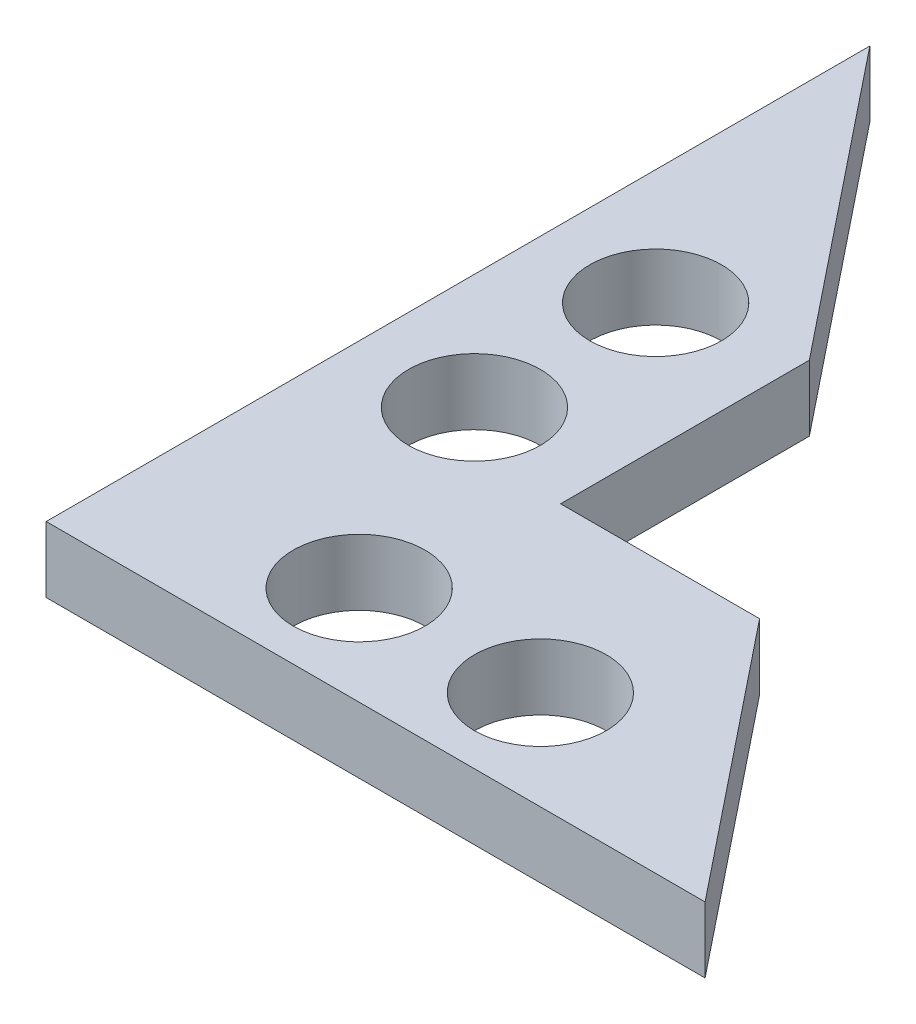
SolidWorks part; units mm, degrees
ref_plane "Front Plane" through (0, 0, 0) normal (0, 0, 1) x (1, 0, 0)
ref_plane "Top Plane" through (0, 0, 0) normal (0, 1, 0) x (1, 0, 0)
ref_plane "Right Plane" through (0, 0, 0) normal (1, 0, 0) x (0, 0, -1)
sketch "Sketch1" plane through (0, 0, 0) normal (0, 1, 0) x (1, 0, 0)
  line L0 (0, 0) -> (0, 63.5)
  line L1 (0, 0) -> (50.8, 0)
  line L2 (0, 63.5) -> (50.8, 0)
extrude "Boss-Extrude1" add sketch "Sketch1" along normal blind 5.08
sketch "Sketch2" plane through (0, 5.08, 0) normal (0, 1, 0) x (1, 0, 0)
  line L0 (0, 0) -> (50.8, 0) construction
  line L1 (0, 63.5) -> (0, 0) construction
  circle A0 centre (8.89, 24.13) radius 5.08
  circle A1 centre (8.89, 38.1) radius 5.08
  circle A2 centre (16.51, 7.62) radius 5.08
  circle A3 centre (30.48, 7.62) radius 5.08
  dimension "D1" = 24.13
  dimension "D2" = 38.1
  dimension "D3" = 16.51
  dimension "D4" = 30.48
  dimension "D5" = 7.62
  dimension "D6" = 8.89
extrude "Cut-Extrude1" cut sketch "Sketch2" against normal blind 7.62
sketch "Sketch3" plane through (0, 5.08, 0) normal (0, 1, 0) x (1, 0, 0)
  line L0 (18.6461, 21.0122) -> (18.6461, 40.1924)
  line L1 (50.8, 0) -> (0, 63.5) construction
  line L2 (18.6461, 21.0122) -> (33.9903, 21.0122)
  line L3 (18.6461, 40.1924) -> (33.9903, 21.0122)
  dimension "D1" = 15.3441
  dimension "D2" = 19.1802
extrude "Cut-Extrude2" cut sketch "Sketch3" against normal blind 7.62
